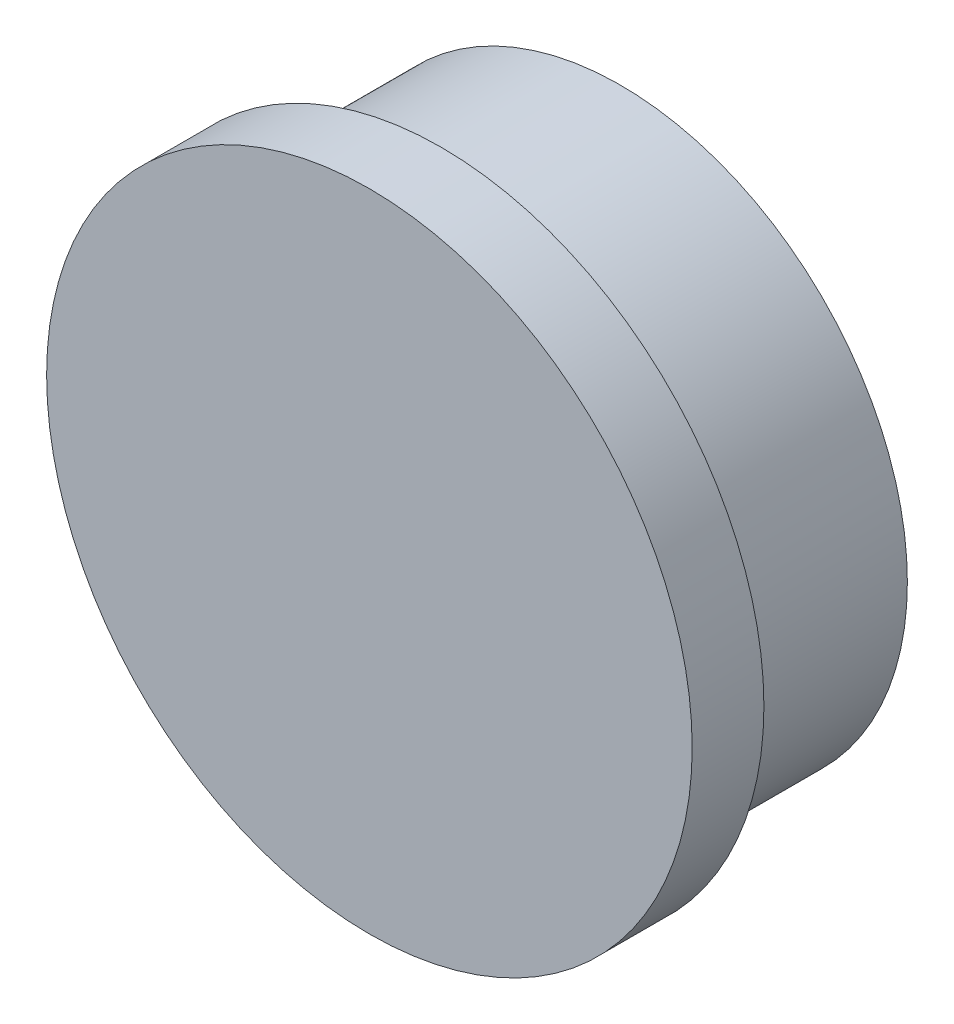
SolidWorks part; units mm, degrees
ref_plane "前视基准面" through (0, 0, 0) normal (0, 0, 1) x (1, 0, 0)
ref_plane "上视基准面" through (0, 0, 0) normal (0, 1, 0) x (1, 0, 0)
ref_plane "右视基准面" through (0, 0, 0) normal (1, 0, 0) x (0, 0, -1)
sketch "草图1" plane through (0, 0, 0) normal (0, 0, 1) x (1, 0, 0)
  circle A0 centre (0, 0) radius 9
extrude "凸台-拉伸1" add sketch "草图1" along normal blind 2
sketch "草图2" plane through (0, 0, 0) normal (0, 0, 1) x (1, 0, 0)
  circle A0 centre (0, 0) radius 8
extrude "凸台-拉伸2" add sketch "草图2" against normal blind 5
